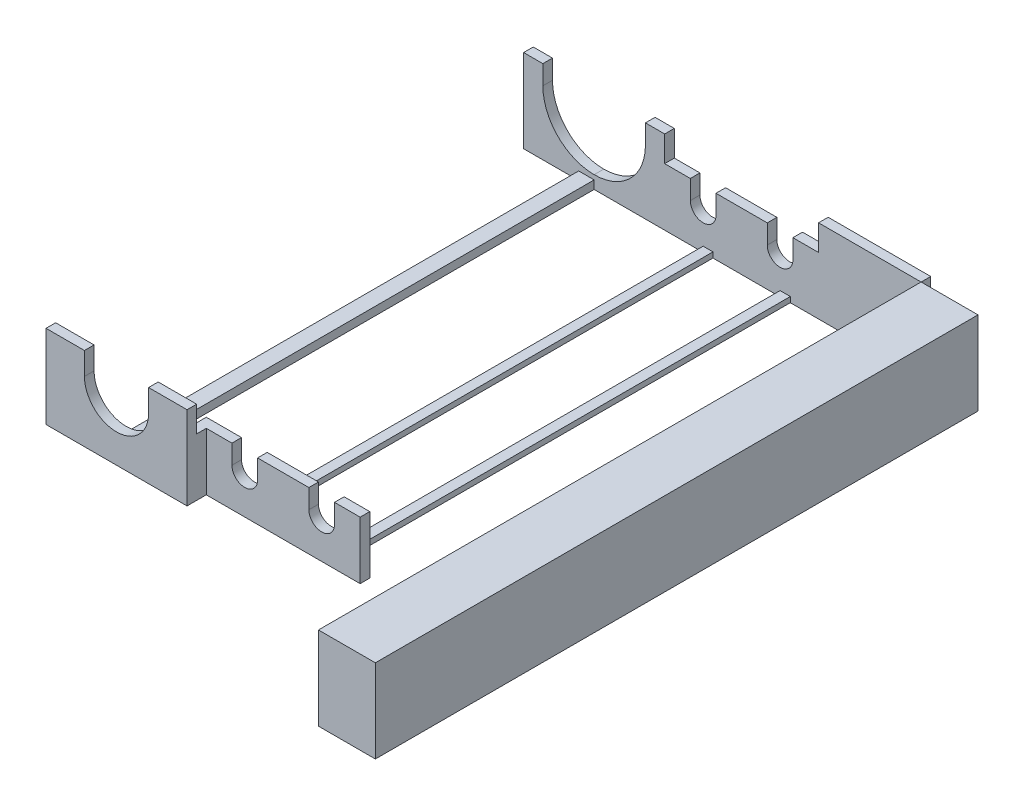
SolidWorks part; units mm, degrees
ref_plane "Alzado" through (0, 0, 0) normal (0, 0, 1) x (1, 0, 0)
ref_plane "Planta" through (0, 0, 0) normal (0, 1, 0) x (1, 0, 0)
ref_plane "Vista lateral" through (0, 0, 0) normal (1, 0, 0) x (0, 0, -1)
sketch "Croquis1" plane through (0, 0, 0) normal (0, 0, 1) x (1, 0, 0)
  line L1 (0, 0) -> (22, 0)
  line L2 (0, 0) -> (0, 13)
  line L3 (0, 13) -> (22, 13)
  line L4 (22, 0) -> (22, 13)
extrude "Saliente-Extruir1" add sketch "Croquis1" along normal blind 1.5
sketch "Croquis2" plane through (0, 0, 1.5) normal (0, 0, 1) x (1, 0, 0)
  line L4 (3, 10) -> (3, 13)
  line L5 (22, 13) -> (0, 13) construction
  line L6 (19, 10) -> (19, 13)
  arc A0 (11, 2) -> (19, 10) centre (11, 10) ccw
  arc A1 (11, 2) -> (3, 10) centre (11, 10) cw
extrude "Cortar-Extruir1" cut sketch "Croquis2" against normal through all and the other way through all
sketch "Croquis3" plane through (0, 0, 1.5) normal (0, 0, 1) x (1, 0, 0)
  line L1 (0, 0) -> (22, 0) construction
  line L4 (11, 0) -> (8.5859, 0)
  line L7 (11, 0) -> (11, 1.2953)
  line L8 (11, 1.2953) -> (8.5859, 1.2953)
  line L9 (8.5859, 0) -> (8.5859, 1.2953)
extrude "Saliente-Extruir2" add sketch "Croquis3" along normal blind 73
sketch "Croquis5" plane through (0, 0, 74.5) normal (0, 0, 1) x (1, 0, 0)
  line L2 (6, 9.5) -> (6, 13)
  line L3 (6, 13) -> (0, 13)
  line L4 (0, 13) -> (0, 0)
  line L5 (0, 0) -> (22, 0)
  line L6 (22, 0) -> (22, 13)
  line L7 (22, 13) -> (16, 13)
  line L8 (16, 13) -> (16, 9.5)
  arc A0 (16, 9.5) -> (6, 9.5) centre (11, 9.5) cw
extrude "Saliente-Extruir3" add sketch "Croquis5" along normal blind 1.5
sketch "Croquis8" plane through (0, 0, 1.5) normal (0, 0, 1) x (1, 0, 0)
  line L0 (34, 0) -> (22, 0)
  line L3 (26, 6) -> (26, 8.9895)
  line L4 (26, 8.9895) -> (22, 8.9895)
  line L5 (22, 0) -> (22, 13) construction
  line L6 (22, 8.9895) -> (22, 0)
  line L8 (30, 6) -> (30, 8.9895)
  line L9 (30, 8.9895) -> (34, 8.9895)
  line L10 (34, 8.9895) -> (34, 0)
  arc A0 (30, 6) -> (26, 6) centre (28, 6) cw
extrude "Saliente-Extruir4" add sketch "Croquis8" against normal blind 1.5
sketch "Croquis10" plane through (0, 0, 1.5) normal (0, 0, 1) x (1, 0, 0)
  line L0 (38, 5.9895) -> (38, 8.9895)
  line L1 (38, 8.9895) -> (34, 8.9895)
  line L2 (34, 8.9895) -> (34, 0)
  line L3 (34, 0) -> (46, 0)
  line L4 (46, 8.9895) -> (46, 0)
  line L5 (42, 5.9895) -> (42, 8.9895)
  line L6 (42, 8.9895) -> (46, 8.9895)
  arc A0 (38, 5.9895) -> (42, 5.9895) centre (40, 5.9895) ccw
extrude "Saliente-Extruir6" add sketch "Croquis10" against normal blind 1.5
sketch "Croquis11" plane through (0, 0, 1.5) normal (0, 0, 1) x (1, 0, 0)
  line L3 (11, 0) -> (46, 0) construction
  line L5 (28, 0) -> (29.5354, 0)
  line L6 (28, 0) -> (28, 0.8413)
  line L7 (28, 0.8413) -> (29.5354, 0.8413)
  line L8 (29.5354, 0) -> (29.5354, 0.8413)
  line L9 (40, 0) -> (41.5967, 0)
  line L10 (40, 0) -> (40, 0.8413)
  line L11 (40, 0.8413) -> (41.5967, 0.8413)
  line L12 (41.5967, 0) -> (41.5967, 0.8413)
extrude "Saliente-Extruir8" add sketch "Croquis11" along normal blind 70
sketch "Croquis12" plane through (0, 0, 71.5) normal (0, 0, 1) x (1, 0, 0)
  line L0 (26, 8.9895) -> (26, 6)
  line L1 (46, 0) -> (22, 0)
  line L2 (46, 0) -> (46, 8.9895)
  line L3 (22, 8.9895) -> (26, 8.9895)
  line L4 (22, 0) -> (22, 8.9895)
  line L5 (30, 8.9895) -> (38, 8.9895)
  line L6 (30, 6) -> (30, 8.9895)
  line L7 (38, 8.9895) -> (38, 5.9895)
  line L8 (42, 8.9895) -> (46, 8.9895)
  line L9 (42, 5.9895) -> (42, 8.9895)
  arc A0 (26, 6) -> (30, 6) centre (28, 6) ccw
  arc A1 (38, 5.9895) -> (42, 5.9895) centre (40, 5.9895) ccw
extrude "Saliente-Extruir9" add sketch "Croquis12" along normal blind 1.5
sketch "Croquis13" plane through (22, 0, 0) normal (-1, 0, 0) x (0, 0, 1)
  line L2 (71.5, 8.9895) -> (74.5, 8.9895)
  line L3 (71.5, 8.9895) -> (71.5, 0)
  line L4 (71.5, 0) -> (74.5, 0)
  line L6 (74.5, 8.9895) -> (74.5, 0)
extrude "Saliente-Extruir10" add sketch "Croquis13" along normal blind 1.5
sketch "Croquis16" plane through (0, 0, 1.5) normal (0, 0, 1) x (1, 0, 0)
  line L1 (46, 0) -> (62, 0)
  line L2 (46, 0) -> (46, 13)
  line L3 (46, 13) -> (62, 13)
  line L4 (62, 0) -> (62, 13)
extrude "Saliente-Extruir11" add sketch "Croquis16" against normal blind 1.5
sketch "Croquis17" plane through (0, 0, 1.5) normal (0, 0, 1) x (1, 0, 0)
  line L1 (62, 13) -> (70.8724, 13)
  line L2 (62, 13) -> (62, 0)
  line L3 (62, 0) -> (70.8724, 0)
  line L4 (70.8724, 13) -> (70.8724, 0)
extrude "Saliente-Extruir13" add sketch "Croquis17" along normal blind 94 separate body
